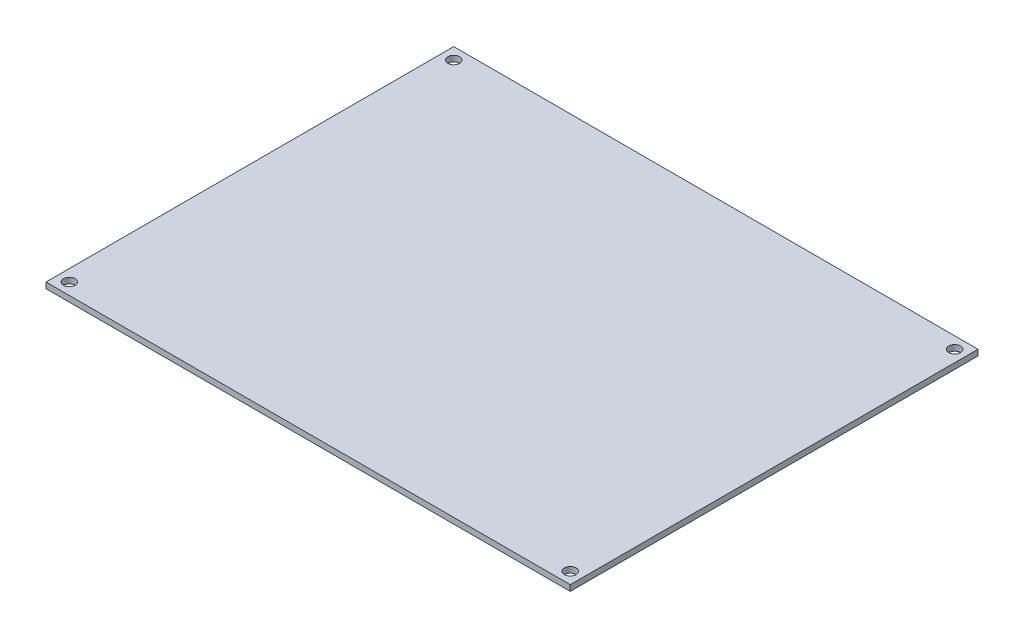
SolidWorks part; units mm, degrees
ref_plane "Front Plane" through (0, 0, 0) normal (0, 0, 1) x (1, 0, 0)
ref_plane "Top Plane" through (0, 0, 0) normal (0, 1, 0) x (1, 0, 0)
ref_plane "Right Plane" through (0, 0, 0) normal (1, 0, 0) x (0, 0, -1)
sketch "Sketch1" plane through (0, 0, 0) normal (0, 1, 0) x (1, 0, 0)
  line L1 (0, 0) -> (90, 0)
  line L2 (0, 0) -> (0, 70)
  line L3 (0, 70) -> (90, 70)
  line L4 (90, 0) -> (90, 70)
  dimension "D1" = 90
  dimension "D2" = 70
extrude "Boss-Extrude1" add sketch "Sketch1" along normal blind 1
sketch "Sketch2" plane through (0, 1, 0) normal (0, 1, 0) x (1, 0, 0)
  line L0 (0, 70) -> (90, 0) construction
  line L2 (2, 2) -> (88, 2) construction
  line L3 (2, 2) -> (2, 68) construction
  line L4 (2, 68) -> (88, 68) construction
  line L5 (88, 2) -> (88, 68) construction
  line L6 (2, 2) -> (88, 68) construction
  line L7 (2, 68) -> (88, 2) construction
  circle A0 centre (88, 68) radius 1
  circle A1 centre (88, 2) radius 1
  circle A2 centre (2, 2) radius 1
  circle A3 centre (2, 68) radius 1
  point P4 (45, 35)
  dimension "D1" = 2
  dimension "D2" = 66
  dimension "D3" = 86
extrude "Cut-Extrude1" cut sketch "Sketch2" against normal blind 10
